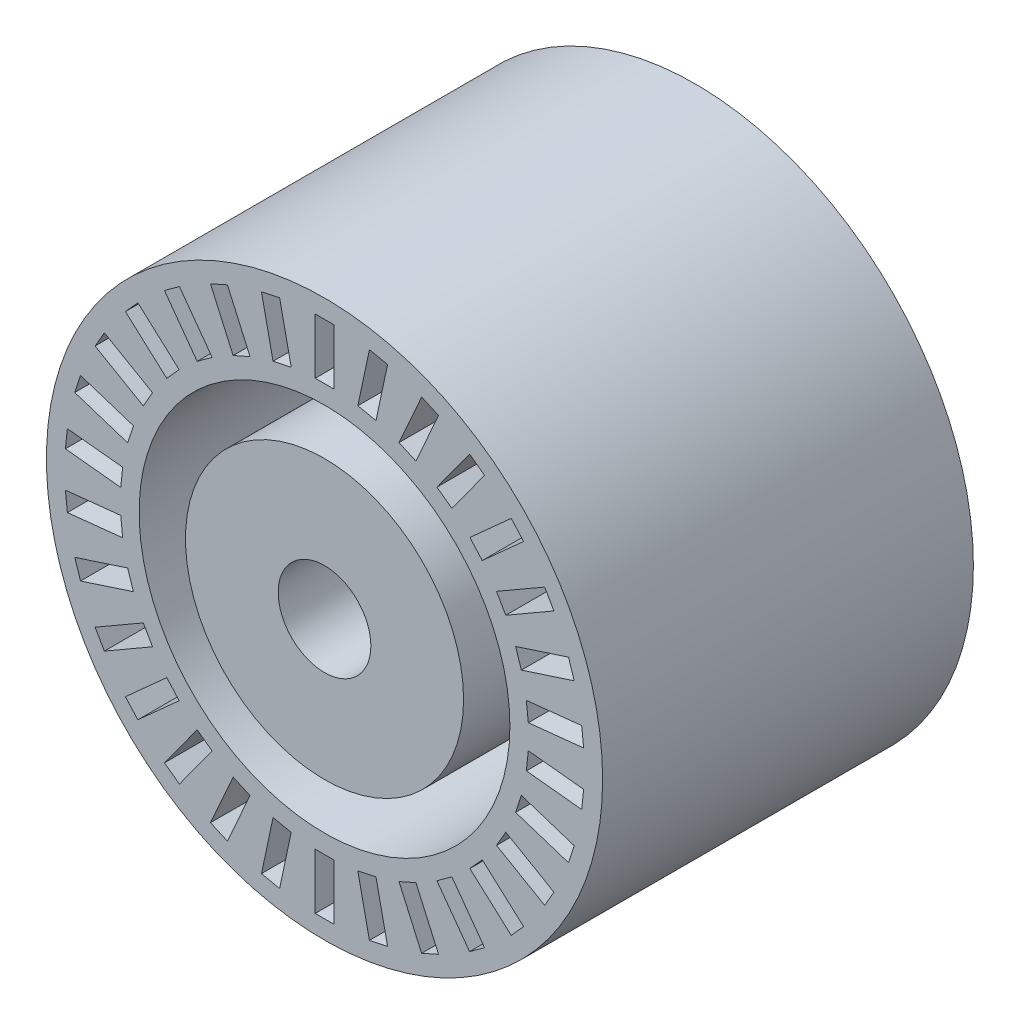
SolidWorks part; units mm, degrees
ref_plane "Front Plane" through (0, 0, 0) normal (0, 0, 1) x (1, 0, 0)
ref_plane "Top Plane" through (0, 0, 0) normal (0, 1, 0) x (1, 0, 0)
ref_plane "Right Plane" through (0, 0, 0) normal (1, 0, 0) x (0, 0, -1)
sketch "Sketch1" plane through (0, 0, 0) normal (0, 0, 1) x (1, 0, 0)
  circle A0 centre (0, 0) radius 15
  circle A1 centre (0, 0) radius 2.5
  dimension "D1" = 30
  dimension "D2" = 5
extrude "Boss-Extrude1" add sketch "Sketch1" along normal blind 20
shell "Shell1" thickness 5
sketch "Sketch2" plane through (0, 0, 0) normal (0, 0, 1) x (1, 0, 0)
  line L0 (0, 14) -> (0, 11)
  dimension "D1" = 3
  dimension "D2" = 11
extrude "Cut-Extrude-Thin1" cut sketch "Sketch2" against normal through all and the other way through all thin thin type mid plane wall 1
pattern_circular "CirPattern1" count 30 over 360 about axis through (0, 0, 0) along (0, 0, 1) of "Cut-Extrude-Thin1"
